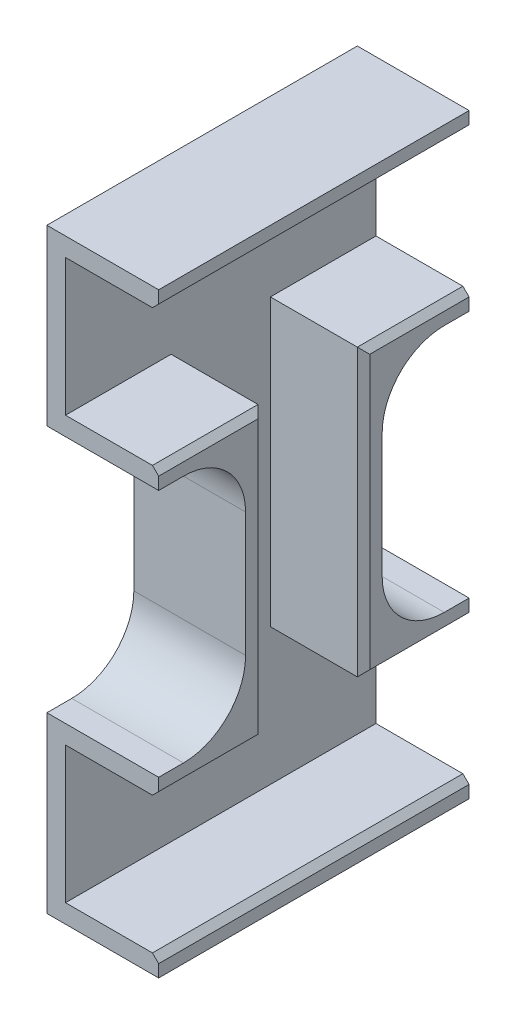
SolidWorks part; units mm, degrees
ref_plane "Front Plane" through (0, 0, 0) normal (0, 0, 1) x (1, 0, 0)
ref_plane "Top Plane" through (0, 0, 0) normal (0, 1, 0) x (1, 0, 0)
ref_plane "Right Plane" through (0, 0, 0) normal (1, 0, 0) x (0, 0, -1)
sketch "Sketch1" plane through (0, 0, 0) normal (1, 0, 0) x (0, 0, -1)
  line L1 (0, 0) -> (50, 0)
  line L2 (0, 0) -> (0, 28)
  line L3 (0, 28) -> (50, 28)
  line L4 (50, 0) -> (50, 28)
  line L5 (14, 28) -> (36, 28)
  line L6 (14, 28) -> (14, 68)
  line L7 (14, 68) -> (36, 68)
  line L8 (36, 28) -> (36, 68)
  line L9 (0, 68) -> (50, 68)
  line L10 (0, 68) -> (0, 96)
  line L11 (0, 96) -> (50, 96)
  line L12 (50, 68) -> (50, 96)
  point P13 (25, 68)
  point P14 (25, 96)
  dimension "D1" = 28
  dimension "D2" = 40
  dimension "D3" = 50
  dimension "22" = 22
extrude "Boss-Extrude1" add sketch "Sketch1" along normal blind 18 contours L9 L12 L11 L10 L7 | L3 L8 L7 L6 | L1 L4 L3 L2
sketch "Sketch2" plane through (18, 0, 0) normal (1, 0, 0) x (0, 0, -1)
  line L0 (0, 0) -> (0, 28) construction
  line L1 (0, 93) -> (50, 93)
  line L2 (0, 93) -> (0, 71)
  line L3 (0, 71) -> (50, 71)
  line L4 (50, 93) -> (50, 71)
  line L5 (17, 71) -> (33, 71)
  line L6 (17, 71) -> (17, 25)
  line L7 (17, 25) -> (33, 25)
  line L8 (33, 71) -> (33, 25)
  line L9 (0, 25) -> (50, 25)
  line L10 (0, 25) -> (0, 3)
  line L11 (0, 3) -> (50, 3)
  line L12 (50, 25) -> (50, 3)
  line L13 (50, 68) -> (50, 96) construction
  line L14 (50, 0) -> (50, 28) construction
  line L15 (0, 0) -> (50, 0) construction
  line L16 (0, 68) -> (0, 96) construction
  point P14 (0, 14)
  point P15 (0, 14)
  point P22 (25, 0)
  point P23 (25, 25)
  point P24 (0, 82)
  line M16 (0, 28) -> (0, 0)
  line M18 (50, 0) -> (50, 28)
  line M22 (50, 68) -> (50, 96)
  line M24 (0, 96) -> (0, 68)
  dimension "D1" = 22
  dimension "D2" = 16
extrude "Cut-Extrude1" cut sketch "Sketch2" against normal blind 15 contours L3 L1 M24 M22 | L8 L3 L6 L7 | L11 L9 L7 M16 M18
fillet "Fillet1" radius 10 4 edges at (9, 28, -36) (9, 68, -36) (9, 28, -14) (9, 68, -14)
chamfer "Chamfer1" distance 1 angle 45 8 edges at (18, 93, -25) (18, 48, -33) (18, 25, -41.5) (18, 25, -8.5) (18, 71, -8.5) (18, 48, -17) (18, 3, -25) (18, 71, -41.5)
